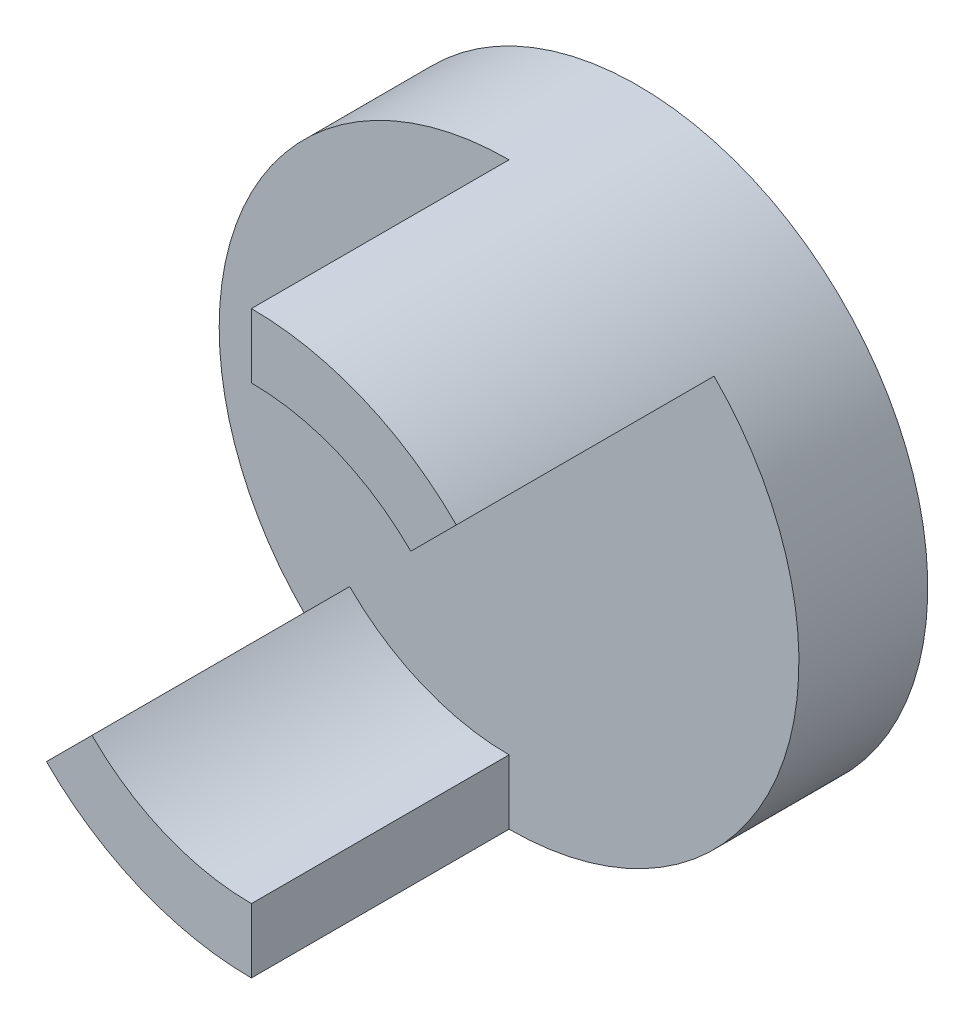
SolidWorks part; units mm, degrees
ref_plane "Front Plane" through (0, 0, 0) normal (0, 0, 1) x (1, 0, 0)
ref_plane "Top Plane" through (0, 0, 0) normal (0, 1, 0) x (1, 0, 0)
ref_plane "Right Plane" through (0, 0, 0) normal (1, 0, 0) x (0, 0, -1)
sketch "Sketch9" plane through (0, 0, 0) normal (0, 0, 1) x (1, 0, 0)
  circle A0 centre (0, 0) radius 2.25
  dimension "D1" = 4.5
extrude "Boss-Extrude1" add sketch "Sketch9" along normal blind 2
shell "Shell1" thickness 1
sketch "Sketch10" plane through (0, 0, 2) normal (0, 0, 1) x (1, 0, 0)
  line L0 (0, 0) -> (0, 2.25)
  line L1 (0, 0) -> (1.591, 1.591)
  line L2 (0, 0) -> (0, -2.25)
  line L3 (0, 0) -> (-1.591, -1.591)
  circle A0 centre (0, 0) radius 2.25
  circle M5 centre (0, 0) radius 1.25
  circle M6 centre (0, 0) radius 2.25
  dimension "D1" = 45
  dimension "D2" = 45
extrude "Cut-Extrude4" cut sketch "Sketch10" against normal blind 1 contours L3 L0 M5 M6 | L2 L1 M5 M6
sketch "Sketch11" plane through (0, 0, 0) normal (0, 0, -1) x (-1, 0, 0)
  circle A0 centre (0, 0) radius 2.25
extrude "Boss-Extrude2" add sketch "Sketch11" along normal blind 1
sketch "Sketch12" plane through (0, 0, 2) normal (0, 0, 1) x (1, 0, 0)
  line L0 (0, 2.25) -> (0, -2.25)
  line L1 (1.591, 1.591) -> (-1.591, -1.591)
  circle A0 centre (0, 0) radius 1.25
  circle A1 centre (0, 0) radius 2.25
  arc M2 (0, 1.25) -> (0.8839, 0.8839) centre (0, 0) cw
  line M3 (0.8839, 0.8839) -> (1.591, 1.591)
  line M5 (0, 2.25) -> (0, 1.25)
extrude "Cut-Extrude5" cut sketch "Sketch12" against normal blind 2 contours L0 A1 A0 M3 | A1 L1 A0 M5 | L0 A0 L1 | L0 A0 L1 | L1 L0 M2 | L1 A0 L0
sketch "Sketch13" plane through (0, 0, 2) normal (0, 0, 1) x (1, 0, 0)
  circle A0 centre (0, 0) radius 1.75
  dimension "D1" = 3.5
extrude "Cut-Extrude6" cut sketch "Sketch13" against normal blind 2
